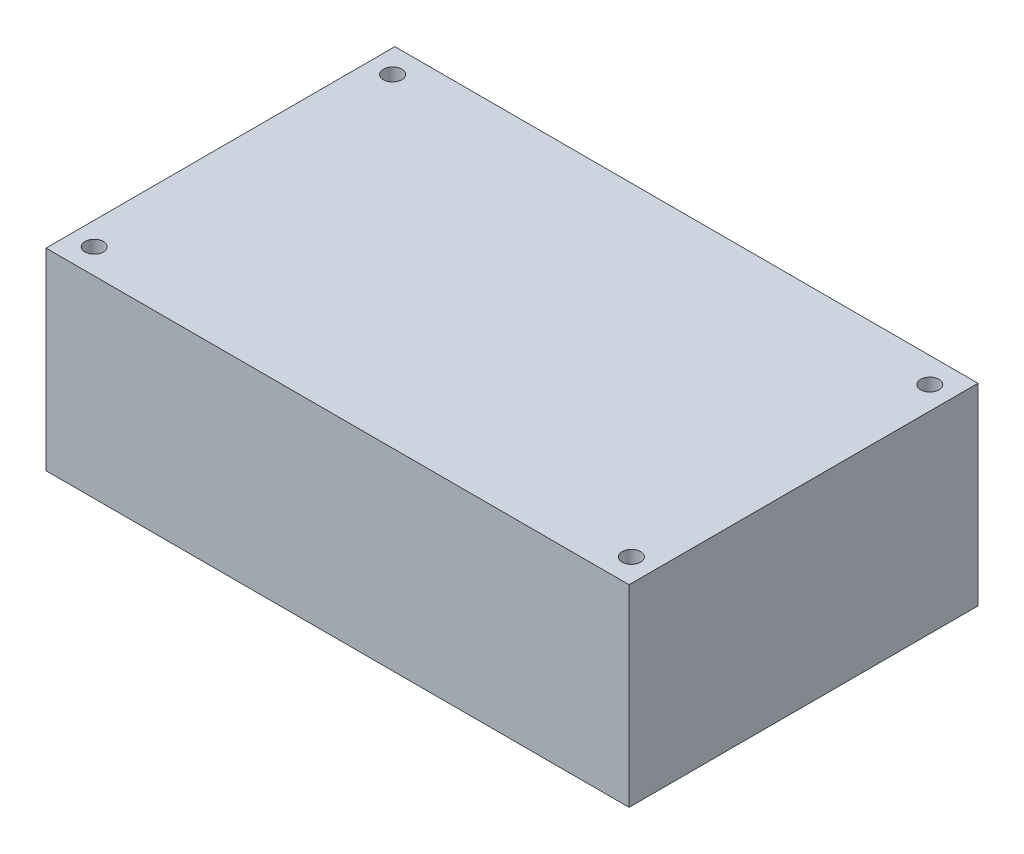
SolidWorks part; units mm, degrees
ref_plane "Front Plane" through (0, 0, 0) normal (0, 0, 1) x (1, 0, 0)
ref_plane "Top Plane" through (0, 0, 0) normal (0, 1, 0) x (1, 0, 0)
ref_plane "Right Plane" through (0, 0, 0) normal (1, 0, 0) x (0, 0, -1)
sketch "Sketch1" plane through (0, 0, 0) normal (0, 1, 0) x (1, 0, 0)
  line L1 (-63.5, -38) -> (63.5, -38)
  line L2 (-63.5, -38) -> (-63.5, 38)
  line L3 (-63.5, 38) -> (63.5, 38)
  line L4 (63.5, -38) -> (63.5, 38)
  line L5 (-63.5, -38) -> (63.5, 38) construction
  line L6 (-63.5, 38) -> (63.5, -38) construction
  point P0 (0, 0)
  dimension "D1" = 127
  dimension "D2" = 76
extrude "Boss-Extrude1" add sketch "Sketch1" along normal blind 42
sketch "Sketch2" plane through (0, 42, 0) normal (0, 1, 0) x (1, 0, 0)
  line L0 (63.5, 38) -> (-63.5, 38) construction
  line L1 (-63.5, 38) -> (-63.5, -38) construction
  line L2 (63.5, -38) -> (63.5, 38) construction
  circle A0 centre (-58.5, 32.5) radius 2
  circle A1 centre (58.5, 32.5) radius 2
  circle A2 centre (58.5, -32.5) radius 2
  circle A3 centre (-58.5, -32.5) radius 2
  dimension "D1" = 4
  dimension "D2" = 5.5
  dimension "D5" = 5
  dimension "D6" = 5
  dimension "D3" = 2
  dimension "D4" = 2
extrude "Cut-Extrude1" cut sketch "Sketch2" against normal through all
